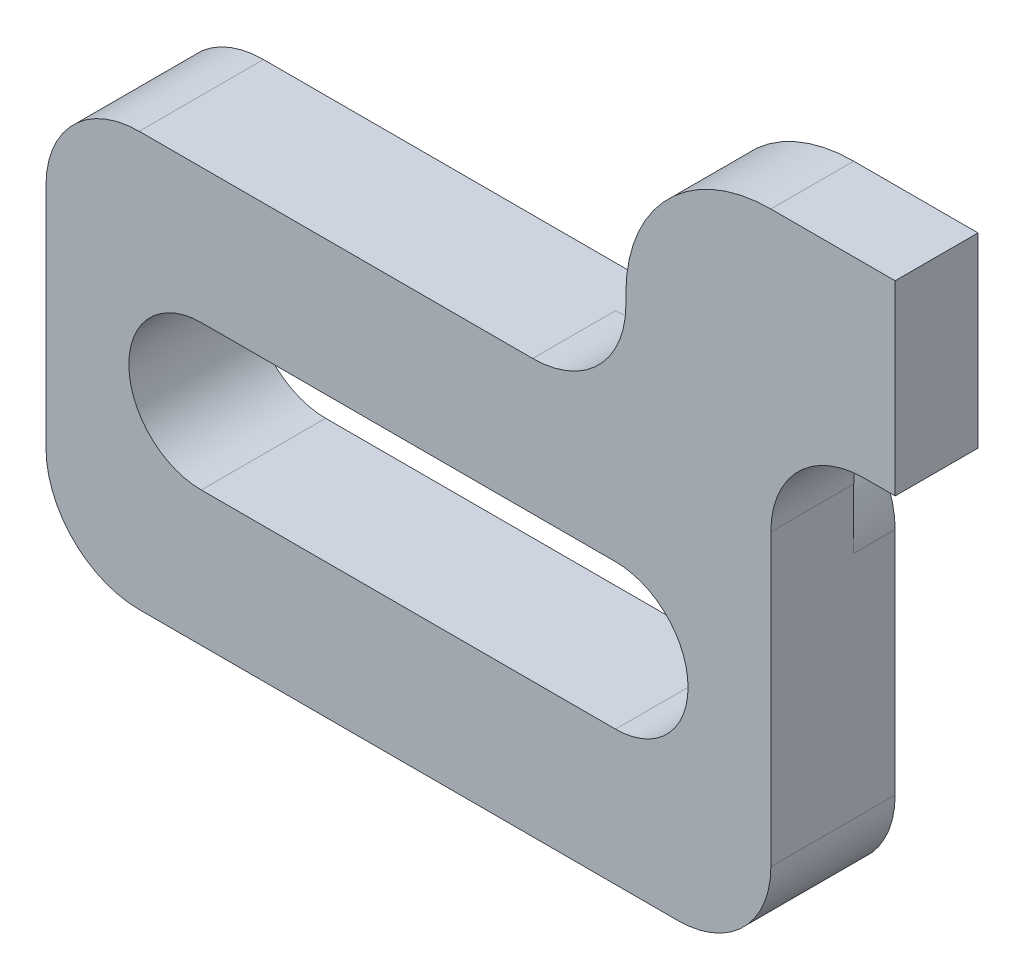
SolidWorks part; units mm, degrees
ref_plane "Ebene vorne" through (0, 0, 0) normal (0, 0, 1) x (1, 0, 0)
ref_plane "Ebene oben" through (0, 0, 0) normal (0, 1, 0) x (1, 0, 0)
ref_plane "Ebene rechts" through (0, 0, 0) normal (1, 0, 0) x (0, 0, -1)
sketch "Skizze1" plane through (0, 0, 0) normal (0, 0, 1) x (1, 0, 0)
  line L0 (3.75, 5) -> (13.75, 5) construction
  line L1 (2.25, 0) -> (15.25, 0)
  line L2 (0, 2.25) -> (0, 7.75)
  line L3 (2.25, 10) -> (11.75, 10)
  line L4 (17.5, 2.25) -> (17.5, 9.25)
  line L5 (19.75, 11.5) -> (20.5, 11.5)
  line L6 (14, 12.25) -> (14, 12.5)
  line L7 (17.5, 16) -> (20.5, 16)
  line L8 (20.5, 11.5) -> (20.5, 16)
  line L9 (3.75, 6.75) -> (13.75, 6.75)
  line L10 (3.75, 3.25) -> (13.75, 3.25)
  arc A0 (3.75, 6.75) -> (3.75, 3.25) centre (3.75, 5) ccw
  arc A1 (13.75, 3.25) -> (13.75, 6.75) centre (13.75, 5) ccw
  arc A2 (15.25, 0) -> (17.5, 2.25) centre (15.25, 2.25) ccw
  arc A3 (2.25, 0) -> (0, 2.25) centre (2.25, 2.25) cw
  arc A4 (0, 7.75) -> (2.25, 10) centre (2.25, 7.75) cw
  arc A5 (14, 12.5) -> (17.5, 16) centre (17.5, 12.5) cw
  arc A6 (19.75, 11.5) -> (17.5, 9.25) centre (19.75, 9.25) ccw
  arc A7 (11.75, 10) -> (14, 12.25) centre (11.75, 12.25) ccw
  point P11 (8.75, 5)
  point P18 (17.5, 0)
  point P21 (0, 0)
  point P24 (0, 10)
  point P27 (14, 16)
  point P32 (14, 10)
  dimension "D9" = 2.25
  dimension "D10" = 3.5
  dimension "D1" = 3.5
  dimension "D2" = 10
  dimension "D3" = 17.5
  dimension "D4" = 8.75
  dimension "D5" = 10
  dimension "D6" = 5
  dimension "D7" = 6
  dimension "D8" = 3
extrude "Aufsatz-Linear austragen1" add sketch "Skizze1" along normal blind 3
sketch "Skizze2" plane through (0, 0, 0) normal (0, 0, -1) x (-1, 0, 0)
  line L1 (0.4736, 10) -> (-20.5, 10)
  line L2 (-20.5, 11.5) -> (-20.5, 17.5)
  line L3 (-20.5, 17.5) -> (0.4736, 17.5)
  line L4 (0.4736, 12.5) -> (0.4736, 17.5)
  line L6 (-20.5, 11.5) -> (-20.5, 10)
  line L11 (0.4736, 12.5) -> (0.4736, 10)
extrude "Schnitt-Linear austragen1" cut sketch "Skizze2" against normal blind 1
sketch "Skizze3" plane through (0, 0, 0) normal (0, 0, -1) x (-1, 0, 0)
  line L0 (-17.6287, 10) -> (-2.25, 10) construction
  line L1 (-17.5, 2.25) -> (-17.5, 9.25) construction
  line L2 (-17.5, 7.8) -> (-18.826, 7.8)
  line L3 (-18.826, 7.8) -> (-18.826, 10.6482)
  line L4 (-18.826, 10.6482) -> (-15.3, 10.6482)
  line L5 (-15.3, 10.6482) -> (-15.3, 10)
  arc A0 (-15.3, 10) -> (-17.5, 7.8) centre (-15.3, 7.8) ccw
  dimension "D1" = 4.4
extrude "Schnitt-Linear austragen2" cut sketch "Skizze3" against normal blind 1
